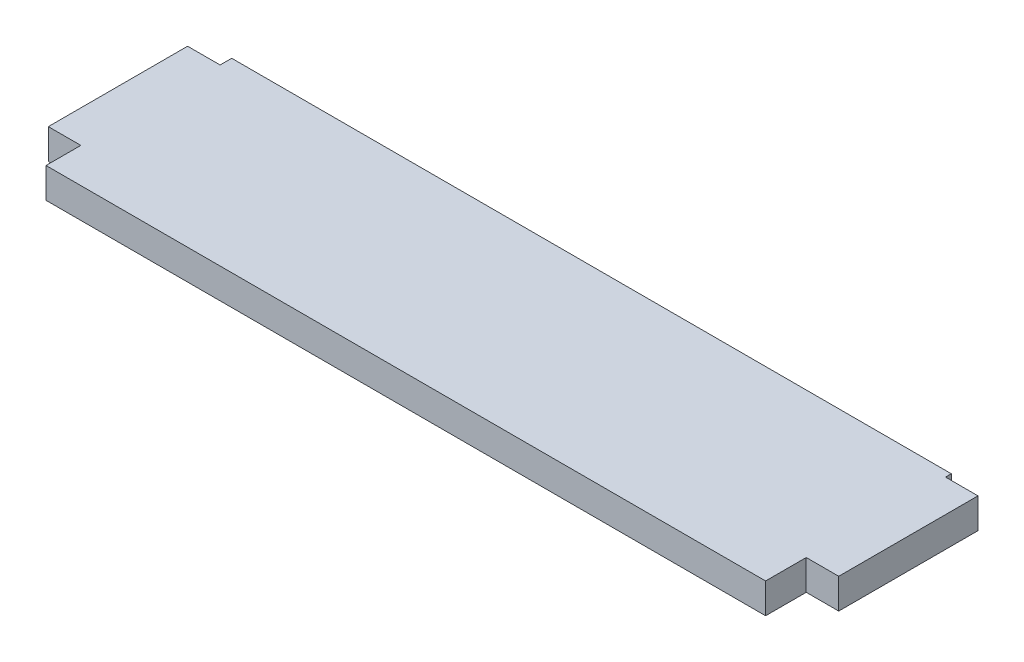
SolidWorks part; units mm, degrees
ref_plane "Front Plane" through (0, 0, 0) normal (0, 0, 1) x (1, 0, 0)
ref_plane "Top Plane" through (0, 0, 0) normal (0, 1, 0) x (1, 0, 0)
ref_plane "Right Plane" through (0, 0, 0) normal (1, 0, 0) x (0, 0, -1)
sketch "Sketch1" plane through (0, 0, 0) normal (0, 1, 0) x (1, 0, 0)
  line L1 (-15.5, 4) -> (15.5, 4)
  line L2 (-15.5, 4) -> (-15.5, -4)
  line L3 (-15.5, -4) -> (15.5, -4)
  line L4 (15.5, 4) -> (15.5, -4)
  line L5 (-15.5, 4) -> (15.5, -4) construction
  line L6 (-15.5, -4) -> (15.5, 4) construction
  point P0 (0, 0)
  dimension "D1" = 31
  dimension "D2" = 8
extrude "Boss-Extrude1" add sketch "Sketch1" along normal blind 1.3
sketch "Sketch2" plane through (0, 0, 0) normal (0, 1, 0) x (1, 0, 0)
  line L0 (-15.5, 4) -> (-15.5, -4) construction
  line L1 (-15.5, 3.5) -> (-16.9, 3.5)
  line L2 (-15.5, 3.5) -> (-15.5, -2.5)
  line L3 (-15.5, -2.5) -> (-16.9, -2.5)
  line L4 (-16.9, 3.5) -> (-16.9, -2.5)
  line L5 (15.5, -4) -> (15.5, 4) construction
  line L6 (15.5, 3.75) -> (16.9, 3.75)
  line L7 (15.5, 3.75) -> (15.5, -2.25)
  line L8 (15.5, -2.25) -> (16.9, -2.25)
  line L9 (16.9, 3.75) -> (16.9, -2.25)
  line L10 (-15.5, -4) -> (15.5, -4) construction
  dimension "D1" = 6
  dimension "D2" = 6
  dimension "D3" = 1.75
  dimension "D4" = 1.5
  dimension "D5" = 1.4
  dimension "D6" = 1.4
extrude "Boss-Extrude2" add sketch "Sketch2" along normal blind 1.3
